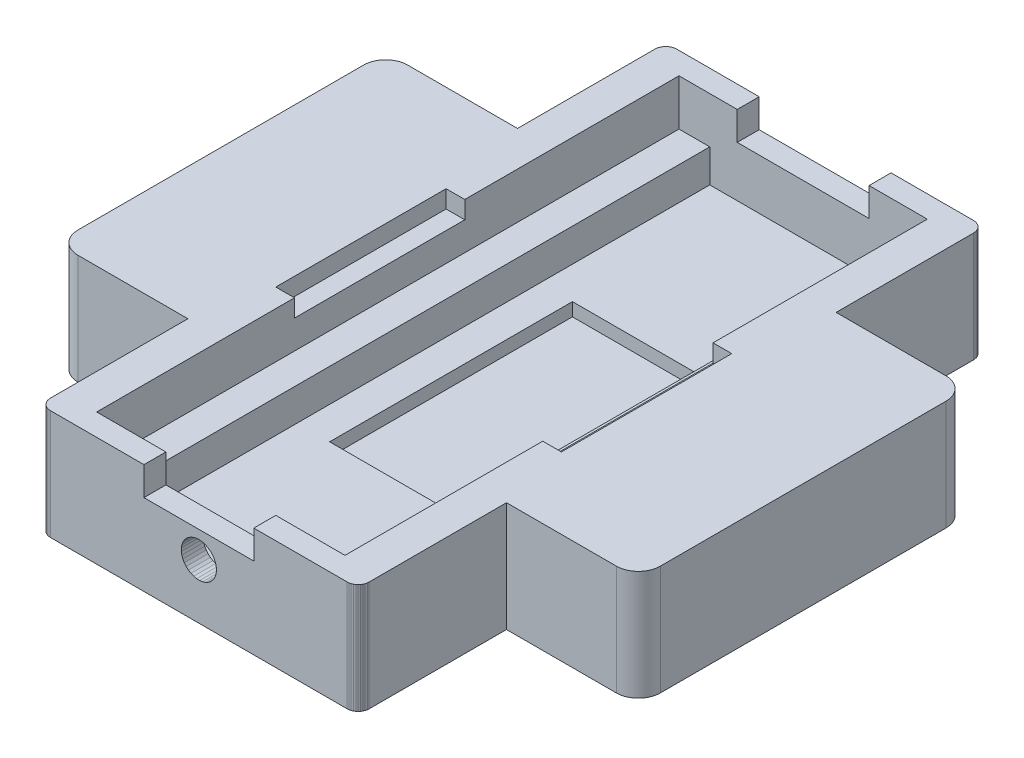
SolidWorks part; units mm, degrees
ref_plane "Front Plane" through (0, 0, 0) normal (0, 0, 1) x (1, 0, 0)
ref_plane "Top Plane" through (0, 0, 0) normal (0, 1, 0) x (1, 0, 0)
ref_plane "Right Plane" through (0, 0, 0) normal (1, 0, 0) x (0, 0, -1)
ref_plane "Plane1" through (0, 0, 0) normal (0, -1, 0) x (1, 0, 0)
sketch "Sketch1" plane through (0, 0, 0) normal (0, -1, 0) x (1, 0, 0)
  line L0 (0.8436, 0.0123) -> (1, 0)
  line L1 (1, 0) -> (28, 0)
  line L2 (28, 0) -> (28.1564, 0.0123)
  line L3 (28.1564, 0.0123) -> (28.309, 0.0489)
  line L4 (28.309, 0.0489) -> (28.454, 0.109)
  line L5 (28.454, 0.109) -> (28.5878, 0.191)
  line L6 (28.5878, 0.191) -> (28.7071, 0.2929)
  line L7 (28.7071, 0.2929) -> (28.809, 0.4122)
  line L8 (28.809, 0.4122) -> (28.891, 0.546)
  line L9 (28.891, 0.546) -> (28.9511, 0.691)
  line L10 (28.9511, 0.691) -> (28.9877, 0.8436)
  line L11 (28.9877, 0.8436) -> (29, 1)
  line L12 (29, 1) -> (29, 56)
  line L13 (29, 56) -> (28.9877, 56.1564)
  line L14 (28.9877, 56.1564) -> (28.9511, 56.309)
  line L15 (28.9511, 56.309) -> (28.891, 56.454)
  line L16 (28.891, 56.454) -> (28.809, 56.5878)
  line L17 (28.809, 56.5878) -> (28.7071, 56.7071)
  line L18 (28.7071, 56.7071) -> (28.5878, 56.809)
  line L19 (28.5878, 56.809) -> (28.454, 56.891)
  line L20 (28.454, 56.891) -> (28.309, 56.9511)
  line L21 (28.309, 56.9511) -> (28.1564, 56.9877)
  line L22 (28.1564, 56.9877) -> (28, 57)
  line L23 (28, 57) -> (1, 57)
  line L24 (1, 57) -> (0.8436, 56.9877)
  line L25 (0.8436, 56.9877) -> (0.691, 56.9511)
  line L26 (0.691, 56.9511) -> (0.546, 56.891)
  line L27 (0.546, 56.891) -> (0.4122, 56.809)
  line L28 (0.4122, 56.809) -> (0.2929, 56.7071)
  line L29 (0.2929, 56.7071) -> (0.191, 56.5878)
  line L30 (0.191, 56.5878) -> (0.109, 56.454)
  line L31 (0.109, 56.454) -> (0.0489, 56.309)
  line L32 (0.0489, 56.309) -> (0.0123, 56.1564)
  line L33 (0.0123, 56.1564) -> (0, 56)
  line L34 (0, 56) -> (0, 1)
  line L35 (0, 1) -> (0.0123, 0.8436)
  line L36 (0.0123, 0.8436) -> (0.0489, 0.691)
  line L37 (0.0489, 0.691) -> (0.109, 0.546)
  line L38 (0.109, 0.546) -> (0.191, 0.4122)
  line L39 (0.191, 0.4122) -> (0.2929, 0.2929)
  line L40 (0.2929, 0.2929) -> (0.4122, 0.191)
  line L41 (0.4122, 0.191) -> (0.546, 0.109)
  line L42 (0.546, 0.109) -> (0.691, 0.0489)
  line L43 (0.691, 0.0489) -> (0.8436, 0.0123)
extrude "Boss-Extrude1" add sketch "Sketch1" against normal blind 10
sketch "Sketch2" plane through (0, 10, 0) normal (0, 1, 0) x (-1, 0, 0)
  line L0 (-23, 2) -> (-6, 2)
  line L1 (-6, 2) -> (-6, 55)
  line L2 (-6, 55) -> (-23, 55)
  line L3 (-23, 55) -> (-23, 2)
extrude "Cut-Extrude1" cut sketch "Sketch2" against normal blind 7.2
ref_plane "Plane2" through (0, 10, 0) normal (0, 1, 0) x (1, 0, 0)
ref_plane "Plane3" through (0, 5.8, 0) normal (0, -1, 0) x (1, 0, 0)
sketch "Sketch4" plane through (0, 5.8, 0) normal (0, -1, 0) x (1, 0, 0)
  line L0 (23, 55) -> (23, 2)
  line L1 (23, 2) -> (25.8, 2)
  line L2 (25.8, 2) -> (25.8, 55)
  line L3 (25.8, 55) -> (23, 55)
extrude "Cut-Extrude2" cut sketch "Sketch4" against normal up to surface up to plane "Plane2"
sketch "Sketch6" plane through (0, 5.8, 0) normal (0, -1, 0) x (1, 0, 0)
  line L0 (3.2, 55) -> (3.2, 2)
  line L1 (3.2, 2) -> (6, 2)
  line L2 (6, 2) -> (6, 55)
  line L3 (6, 55) -> (3.2, 55)
extrude "Cut-Extrude3" cut sketch "Sketch6" against normal up to surface up to plane "Plane2"
sketch "Sketch7" plane through (0, 0, 57) normal (0, 0, 1) x (1, 0, 0)
  line L0 (19.5, 10) -> (9.5, 10)
  line L1 (9.5, 10) -> (9.5, 7.4)
  line L2 (9.5, 7.4) -> (19.5, 7.4)
  line L3 (19.5, 7.4) -> (19.5, 10)
extrude "Cut-Extrude4" cut sketch "Sketch7" against normal up to next
sketch "Sketch8" plane through (0, 0, 0) normal (0, 0, -1) x (-1, 0, 0)
  line L0 (-8.5, 10) -> (-20.5, 10)
  line L1 (-20.5, 10) -> (-20.5, 7.4)
  line L2 (-20.5, 7.4) -> (-8.5, 7.4)
  line L3 (-8.5, 7.4) -> (-8.5, 10)
extrude "Cut-Extrude5" cut sketch "Sketch8" against normal up to next
sketch "Sketch9" plane through (0, 0, 55) normal (0, 0, -1) x (-1, 0, 0)
  line L0 (-16.0086, 4.467) -> (-15.8968, 4.2197)
  line L1 (-15.8968, 4.2197) -> (-15.7449, 3.9948)
  line L2 (-15.7449, 3.9948) -> (-15.5571, 3.7989)
  line L3 (-15.5571, 3.7989) -> (-15.3389, 3.6376)
  line L4 (-15.3389, 3.6376) -> (-15.0966, 3.5154)
  line L5 (-15.0966, 3.5154) -> (-14.8371, 3.4359)
  line L6 (-14.8371, 3.4359) -> (-14.5679, 3.4014)
  line L7 (-14.5679, 3.4014) -> (-14.2968, 3.413)
  line L8 (-14.2968, 3.413) -> (-14.0315, 3.4701)
  line L9 (-14.0315, 3.4701) -> (-13.7797, 3.5713)
  line L10 (-13.7797, 3.5713) -> (-13.5486, 3.7136)
  line L11 (-13.5486, 3.7136) -> (-13.3449, 3.8929)
  line L12 (-13.3449, 3.8929) -> (-13.1744, 4.104)
  line L13 (-13.1744, 4.104) -> (-13.042, 4.341)
  line L14 (-13.042, 4.341) -> (-12.9516, 4.5968)
  line L15 (-12.9516, 4.5968) -> (-12.9058, 4.8643)
  line L16 (-12.9058, 4.8643) -> (-12.9058, 5.1357)
  line L17 (-12.9058, 5.1357) -> (-12.9516, 5.4032)
  line L18 (-12.9516, 5.4032) -> (-13.042, 5.659)
  line L19 (-13.042, 5.659) -> (-13.1744, 5.896)
  line L20 (-13.1744, 5.896) -> (-13.3449, 6.1071)
  line L21 (-13.3449, 6.1071) -> (-13.5486, 6.2864)
  line L22 (-13.5486, 6.2864) -> (-13.7797, 6.4287)
  line L23 (-13.7797, 6.4287) -> (-14.0315, 6.5299)
  line L24 (-14.0315, 6.5299) -> (-14.2968, 6.587)
  line L25 (-14.2968, 6.587) -> (-14.5679, 6.5986)
  line L26 (-14.5679, 6.5986) -> (-14.8371, 6.5641)
  line L27 (-14.8371, 6.5641) -> (-15.0966, 6.4846)
  line L28 (-15.0966, 6.4846) -> (-15.3389, 6.3624)
  line L29 (-15.3389, 6.3624) -> (-15.5571, 6.2011)
  line L30 (-15.5571, 6.2011) -> (-15.7449, 6.0052)
  line L31 (-15.7449, 6.0052) -> (-15.8968, 5.7803)
  line L32 (-15.8968, 5.7803) -> (-16.0086, 5.533)
  line L33 (-16.0086, 5.533) -> (-16.077, 5.2704)
  line L34 (-16.077, 5.2704) -> (-16.1, 5)
  line L35 (-16.1, 5) -> (-16.077, 4.7296)
  line L36 (-16.077, 4.7296) -> (-16.0086, 4.467)
extrude "Cut-Extrude6" cut sketch "Sketch9" against normal through all
sketch "Sketch10" plane through (0, 10, 0) normal (0, 1, 0) x (-1, 0, 0)
  line L0 (-3.2, 21.5) -> (-1.5, 21.5)
  line L1 (-1.5, 21.5) -> (-1.5, 37)
  line L2 (-1.5, 37) -> (-3.2, 37)
  line L3 (-3.2, 37) -> (-3.2, 21.5)
extrude "Cut-Extrude7" cut sketch "Sketch10" against normal blind 1.6
sketch "Sketch11" plane through (0, 10, 0) normal (0, 1, 0) x (-1, 0, 0)
  line L0 (-25.8, 37) -> (-27.5, 37)
  line L1 (-27.5, 37) -> (-27.5, 21.5)
  line L2 (-27.5, 21.5) -> (-25.8, 21.5)
  line L3 (-25.8, 21.5) -> (-25.8, 37)
extrude "Cut-Extrude8" cut sketch "Sketch11" against normal blind 1.6
sketch "Sketch12" plane through (0, 2.8, 0) normal (0, 1, 0) x (-1, 0, 0)
  line L0 (-20.05, 17.45) -> (-8.95, 17.45)
  line L1 (-8.95, 17.45) -> (-8.95, 39.55)
  line L2 (-8.95, 39.55) -> (-20.05, 39.55)
  line L3 (-20.05, 39.55) -> (-20.05, 17.45)
extrude "Cut-Extrude9" cut sketch "Sketch12" against normal blind 1.2
sketch "Sketch13" plane through (0, 0, 0) normal (-1, 0, 0) x (0, 0, 1)
  line L0 (56, 10) -> (1, 10) construction
  line L1 (13.5, 10) -> (43.5, 10)
  line L2 (13.5, 10) -> (13.5, 0)
  line L3 (13.5, 0) -> (43.5, 0)
  line L4 (43.5, 10) -> (43.5, 0)
  line L5 (13.5, 10) -> (43.5, 0) construction
  line L6 (13.5, 0) -> (43.5, 10) construction
  line L7 (56, 0) -> (1, 0) construction
  line L8 (28.5, 10) -> (28.5, 0) construction
  point P4 (28.5, 5)
  point P11 (0, 0)
  point P12 (28.5, 5)
  dimension "D1" = 30
extrude "Boss-Extrude2" add sketch "Sketch13" along normal blind 12
sketch "Sketch14" plane through (29, 0, 0) normal (1, 0, 0) x (0, 0, -1)
  line L1 (-43.5, 10) -> (-13.5, 10)
  line L2 (-43.5, 10) -> (-43.5, 0)
  line L3 (-43.5, 0) -> (-13.5, 0)
  line L4 (-13.5, 10) -> (-13.5, 0)
  line L5 (-43.5, 10) -> (-13.5, 0) construction
  line L6 (-43.5, 0) -> (-13.5, 10) construction
  point P4 (-28.5, 5)
extrude "Boss-Extrude3" add sketch "Sketch14" along normal blind 12
fillet "Fillet1" radius 2 4 edges at (-12, 5, 13.5) (-12, 5, 43.5) (41, 5, 43.5) (41, 5, 13.5)
sketch "Sketch15" plane through (0, 10, 0) normal (0, 1, 0) x (1, 0, 0)
  line L0 (-5, -13.5) -> (-5, -43.5) construction
  line L1 (-10, -13.5) -> (0, -13.5) construction
  line L2 (-10, -43.5) -> (0, -43.5) construction
  line L3 (34, -13.5) -> (34, -43.5) construction
  line L4 (39, -13.5) -> (29, -13.5) construction
  line L5 (39, -43.5) -> (29, -43.5) construction
  line L6 (-5, -17.5) -> (34, -39.5) construction
  circle A0 centre (-5, -17.5) radius 1.5
  circle A1 centre (-5, -39.5) radius 1.5
  circle A2 centre (34, -17.5) radius 1.5
  circle A3 centre (34, -39.5) radius 1.5
  point P20 (14.5, -28.5)
  point P21 (-5, -28.5)
  dimension "D1" = 3
  dimension "D2" = 22
